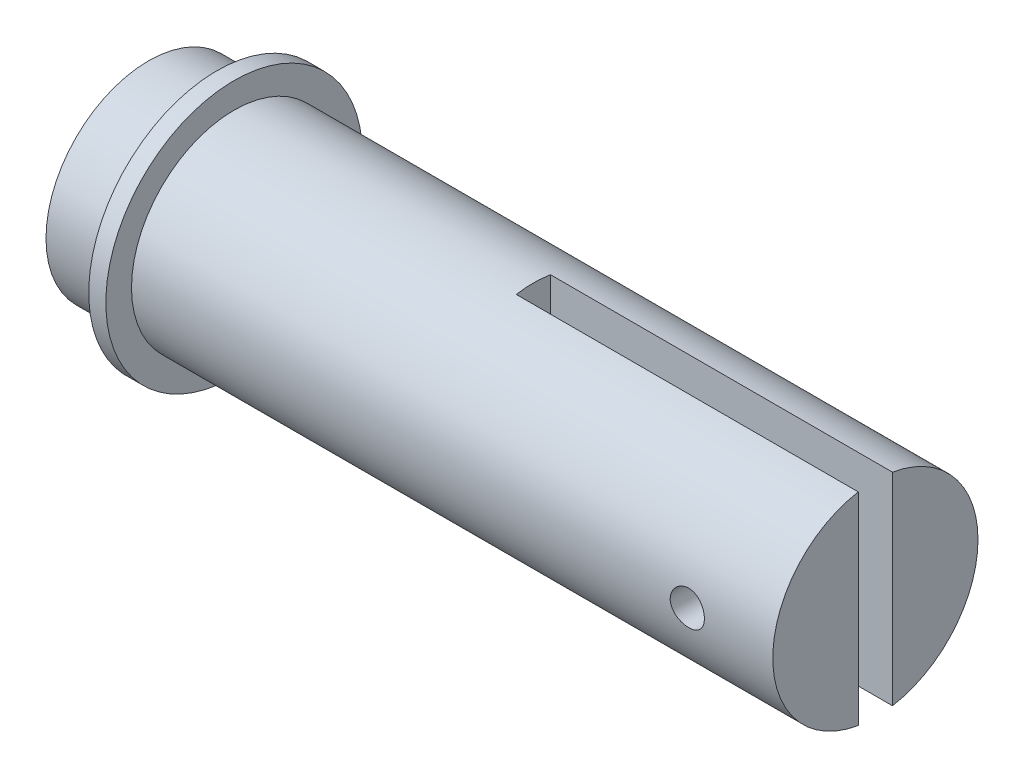
SolidWorks part; units mm, degrees
material "6061 合金"
ref_plane "前视基准面" through (0, 0, 0) normal (0, 0, 1) x (1, 0, 0)
ref_plane "上视基准面" through (0, 0, 0) normal (0, 1, 0) x (1, 0, 0)
ref_plane "右视基准面" through (0, 0, 0) normal (1, 0, 0) x (0, 0, -1)
other "Configuration Table"
sketch "草图1" plane through (0, 0, 0) normal (0, 1, 0) x (1, 0, 0)
  circle A0 centre (0, 0) radius 2
  dimension "D1" = 4
sketch "草图2" plane through (0, 0, 0) normal (1, 0, 0) x (0, 0, -1)
  circle A0 centre (0, 0) radius 12
  dimension "D1" = 24
extrude "凸台-拉伸1" add sketch "草图2" along normal blind 80 and the other way blind 5 contours A0
extrude "切除-拉伸1" cut sketch "草图1" against normal blind 80
ref_plane "基准面1" through (5, 0, 0) normal (1, 0, 0) x (0, 0, -1)
sketch "草图4" plane through (5, 0, 0) normal (1, 0, 0) x (0, 0, -1)
  circle A0 centre (0, 0) radius 15
extrude "凸台-拉伸2" add sketch "草图4" against normal blind 2
sketch "草图7" plane through (80, 0, 0) normal (1, 0, 0) x (0, 0, -1)
  line L0 (-2, 11.8322) -> (-2, -11.8322)
  line L1 (2, 11.8322) -> (2, -11.8322)
  circle A0 centre (0, 0) radius 12 construction
  circle A1 centre (0, 0) radius 12
  circle M3 centre (0, 0) radius 12
  dimension "D1" = 2
  dimension "D2" = 2
extrude "切除-拉伸2" cut sketch "草图7" against normal blind 40 contours L1 L0 M3
sketch "草图8" plane through (0, 0, -2) normal (0, 0, 1) x (1, 0, 0)
  line L0 (80, -11.8322) -> (80, 11.8322) construction
  circle A0 centre (70, 0) radius 2
  dimension "D2" = 4
  dimension "D1" = 10
extrude "切除-拉伸3" cut sketch "草图8" against normal blind 40 and the other way blind 40
sketch "草图10" plane through (0, 0, 0) normal (1, 0, 0) x (0, 0, -1)
  circle A0 centre (0, -8) radius 1
  arc A1 (-2, -11.8322) -> (2, -11.8322) centre (0, 0) ccw construction
  dimension "D1" = 2
  dimension "D2" = 8
extrude "切除-拉伸4" cut sketch "草图10" against normal through all
sketch "草图12" plane through (0, 0, 0) normal (0, 1, 0) x (1, 0, 0)
  line L0 (3, 15) -> (3, -15) construction
  line L1 (3, 9.6865) -> (80, 9.6865)
  line L2 (80, 2) -> (80, 12) construction
  line L3 (-16.5, 0) -> (16.5, 0) construction
sketch "草图14" plane through (0, 0, 0) normal (0, 0, 1) x (1, 0, 0)
  line L0 (70, 0) -> (5, 0)
  line L1 (3, 0) -> (80, 0) construction
  line L2 (5, -16.5) -> (5, 16.5) construction
